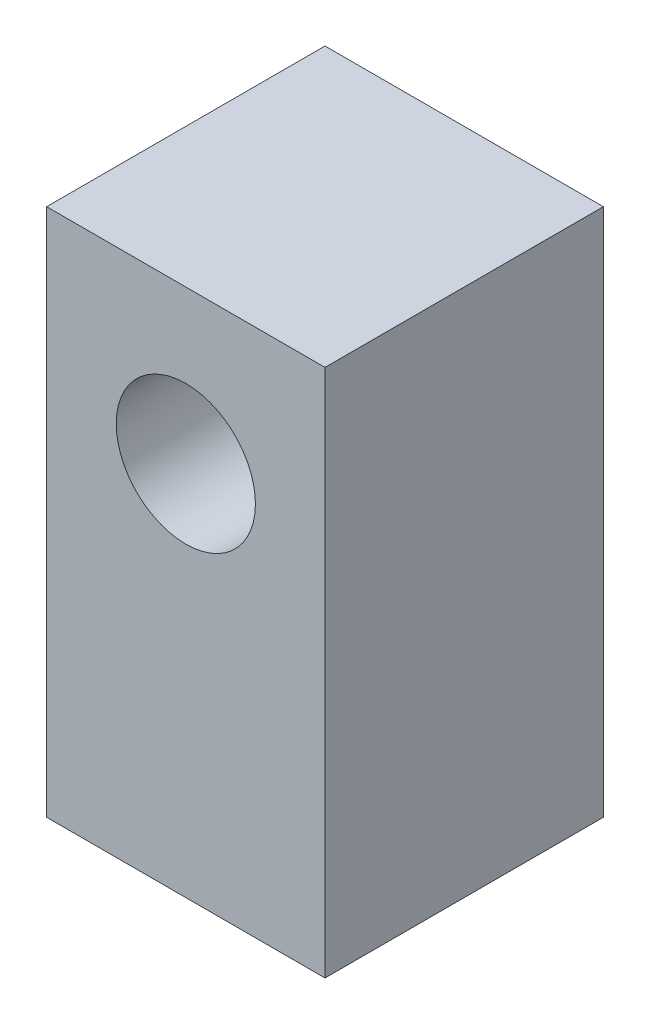
SolidWorks part; units mm, degrees
material "1060-H16"
ref_plane "Спереди" through (0, 0, 0) normal (0, 0, 1) x (1, 0, 0)
ref_plane "Сверху" through (0, 0, 0) normal (0, 1, 0) x (1, 0, 0)
ref_plane "Справа" through (0, 0, 0) normal (1, 0, 0) x (0, 0, -1)
sketch "Эскиз1" plane through (0, 0, 0) normal (0, 0, 1) x (1, 0, 0)
  line L1 (0, 0) -> (10, 0)
  line L2 (0, 0) -> (0, 19)
  line L3 (0, 19) -> (10, 19)
  line L4 (10, 0) -> (10, 19)
  dimension "D1" = 10
  dimension "D2" = 19
extrude "Бобышка-Вытянуть1" add sketch "Эскиз1" along normal blind 10
sketch "Эскиз2" plane through (0, 0, 0) normal (0, 0, -1) x (-1, 0, 0)
  line L0 (-5, 19) -> (-5, 0) construction
  line L1 (-10, 19) -> (0, 19) construction
  circle A0 centre (-5, 13.5) radius 2.5
  dimension "D1" = 5
  dimension "D2" = 5.5
extrude "Вырез-Вытянуть1" cut sketch "Эскиз2" against normal blind 10
